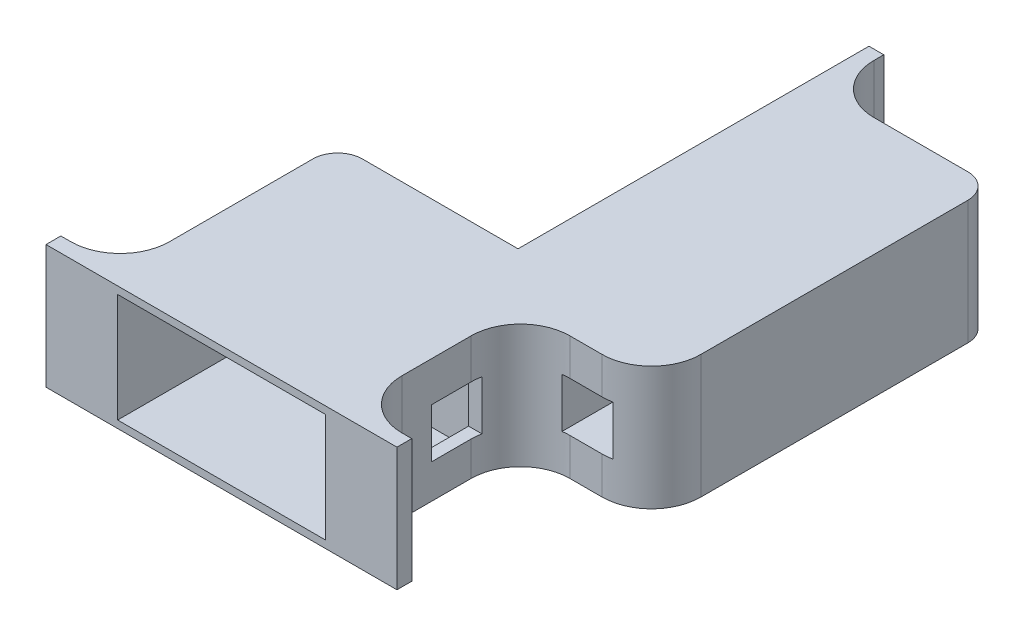
SolidWorks part; units mm, degrees
ref_plane "Front Plane" through (0, 0, 0) normal (0, 0, 1) x (1, 0, 0)
ref_plane "Top Plane" through (0, 0, 0) normal (0, 1, 0) x (1, 0, 0)
ref_plane "Right Plane" through (0, 0, 0) normal (1, 0, 0) x (0, 0, -1)
sketch "Sketch1" plane through (0, 0, 0) normal (0, 1, 0) x (1, 0, 0)
  line L0 (0, -18.5) -> (0, -9.2321)
  line L1 (-23.5, -18.5) -> (23.5, -18.5)
  line L2 (-23.5, -18.5) -> (-23.5, 18.5)
  line L3 (-23.5, 18.5) -> (23.5, 18.5)
  line L4 (23.5, -18.5) -> (23.5, 18.5)
  line L5 (-23.5, -18.5) -> (23.5, 18.5) construction
  line L6 (-23.5, 18.5) -> (23.5, -18.5) construction
  line L7 (-23.5, 18.5) -> (50, 18.5)
  line L8 (-23.5, 18.5) -> (-23.5, 28.5)
  line L9 (-23.5, 28.5) -> (50, 28.5)
  line L10 (50, 18.5) -> (50, 28.5)
  line L11 (50, 28.5) -> (13, 28.5)
  line L12 (50, 28.5) -> (50, 40.5)
  line L13 (50, 40.5) -> (13, 40.5)
  line L14 (13, 28.5) -> (13, 40.5)
  line L15 (13, 40.5) -> (50, 40.5)
  line L16 (13, 40.5) -> (13, 87.5)
  line L17 (13, 87.5) -> (50, 87.5)
  line L18 (50, 40.5) -> (50, 87.5)
  line L19 (23.5, -18.5) -> (35.5, -18.5)
  line L20 (23.5, -18.5) -> (23.5, -15.5)
  line L21 (23.5, -15.5) -> (35.5, -15.5)
  line L22 (35.5, -18.5) -> (35.5, -15.5)
  line L23 (0, -55) -> (0, 55) construction
  line L24 (-23.5, -15.5) -> (-35.5, -15.5)
  line L25 (-35.5, -18.5) -> (-35.5, -15.5)
  line L26 (-23.5, -18.5) -> (-35.5, -18.5)
  line L27 (-23.5, -18.5) -> (-23.5, -15.5)
  line L28 (13, 87.5) -> (13, 99.5)
  line L29 (13, 99.5) -> (16, 99.5)
  line L30 (16, 99.5) -> (16, 87.5)
  line L31 (13.5, -18.5) -> (13.5, -38.5)
  line L32 (13.5, -38.5) -> (13.5, 54.8219)
  line L33 (13, 87.5) -> (16, 87.5)
  point P0 (0, 0)
  dimension "D1" = 47
  dimension "D2" = 37
  dimension "D3" = 10
  dimension "D4" = 37
  dimension "D5" = 12
  dimension "D6" = 47
  dimension "D7" = 12
  dimension "D8" = 3
  dimension "D9" = 12
  dimension "D10" = 3
  dimension "D11" = 20
  dimension "D12" = 10
  dimension "D13" = 73.5
extrude "Boss-Extrude1" add sketch "Sketch1" along normal blind 25
sketch "Sketch2" plane through (0, 0, 18.5) normal (0, 0, 1) x (1, 0, 0)
  line L0 (0, 25) -> (0, 0) construction
  line L1 (-35.5, 25) -> (35.5, 25) construction
  line L3 (-21, 1.5) -> (21, 1.5)
  line L4 (-21, 1.5) -> (-21, 23.5)
  line L5 (-21, 23.5) -> (21, 23.5)
  line L6 (21, 1.5) -> (21, 23.5)
  line L7 (-21, 1.5) -> (21, 23.5) construction
  line L8 (-21, 23.5) -> (21, 1.5) construction
  point P5 (0, 12.5)
  dimension "D1" = 42
  dimension "D2" = 22
extrude "Cut-Extrude1" cut sketch "Sketch2" against normal blind 30.5
sketch "Sketch3" plane through (13, 0, 0) normal (-1, 0, 0) x (0, 0, 1)
  line L0 (-99.5, 25) -> (-28.6346, 0) construction
  line L1 (47.025, 0) -> (-47.025, 0) construction
  line L2 (-28.6346, 0) -> (-28.5, 25) construction
  line L3 (-28.5, 25) -> (-28.5, 0) construction
  line L4 (-28.5, 25) -> (-99.5, 25) construction
  line L5 (-28.5, 25) -> (-99.4131, 0) construction
  line L7 (-85.0673, 1.5) -> (-43.0673, 1.5)
  line L8 (-85.0673, 1.5) -> (-85.0673, 23.5)
  line L9 (-85.0673, 23.5) -> (-43.0673, 23.5)
  line L10 (-43.0673, 1.5) -> (-43.0673, 23.5)
  line L11 (-85.0673, 1.5) -> (-43.0673, 23.5) construction
  line L12 (-85.0673, 23.5) -> (-43.0673, 1.5) construction
  point P5 (-64.0673, 12.5)
  dimension "D1" = 42
  dimension "D2" = 22
extrude "Cut-Extrude2" cut sketch "Sketch3" against normal blind 30.5
fillet "Fillet1" radius 10 5 edges at (16, 12.5, -87.5) (50, 12.5, -18.5) (23.5, 12.5, -18.5) (23.5, 12.5, 15.5) (-23.5, 12.5, 15.5)
fillet "Fillet2" radius 5 1 edges at (-23.5, 12.5, -28.5)
fillet "Fillet3" radius 5 1 edges at (50, 12.5, -87.5)
sketch "Sketch5" plane through (21, 0, 0) normal (-1, 0, 0) x (0, 0, 1)
  line L0 (-12, 23.5) -> (-12, 0.3525) construction
  line L1 (-12, 1.5) -> (-12, 23.5) construction
  line L2 (-12, 11.9263) -> (5.8181, 11.9263)
  line L4 (-10.5, 6.9263) -> (-0.5, 6.9263)
  line L5 (-10.5, 6.9263) -> (-10.5, 16.9263)
  line L6 (-10.5, 16.9263) -> (-0.5, 16.9263)
  line L7 (-0.5, 6.9263) -> (-0.5, 16.9263)
  line L8 (-10.5, 6.9263) -> (-0.5, 16.9263) construction
  line L9 (-10.5, 16.9263) -> (-0.5, 6.9263) construction
  point P7 (-5.5, 11.9263)
  dimension "D1" = 1.5
  dimension "D2" = 10
  dimension "D3" = 10
extrude "Cut-Extrude3" cut sketch "Sketch5" against normal blind 30.5 contours L4 L7 L2 L5 | L2 L7 L6 L5
sketch "Sketch6" plane through (0, 0, -43.0673) normal (0, 0, -1) x (-1, 0, 0)
  line L0 (-43.5, 23.5) -> (-43.5, 1.596) construction
  line L1 (-43.5, 1.5) -> (-43.5, 23.5) construction
  line L2 (-43.5, 1.596) -> (-43.5, 12.548) construction
  line L3 (-43.5, 12.548) -> (-37, 12.548) construction
  line L5 (-42, 7.548) -> (-32, 7.548)
  line L6 (-42, 7.548) -> (-42, 17.548)
  line L7 (-42, 17.548) -> (-32, 17.548)
  line L8 (-32, 7.548) -> (-32, 17.548)
  line L9 (-42, 7.548) -> (-32, 17.548) construction
  line L10 (-42, 17.548) -> (-32, 7.548) construction
  dimension "D1" = 1.5
  dimension "D2" = 10
  dimension "D3" = 10
extrude "Cut-Extrude4" cut sketch "Sketch6" against normal blind 30.5
